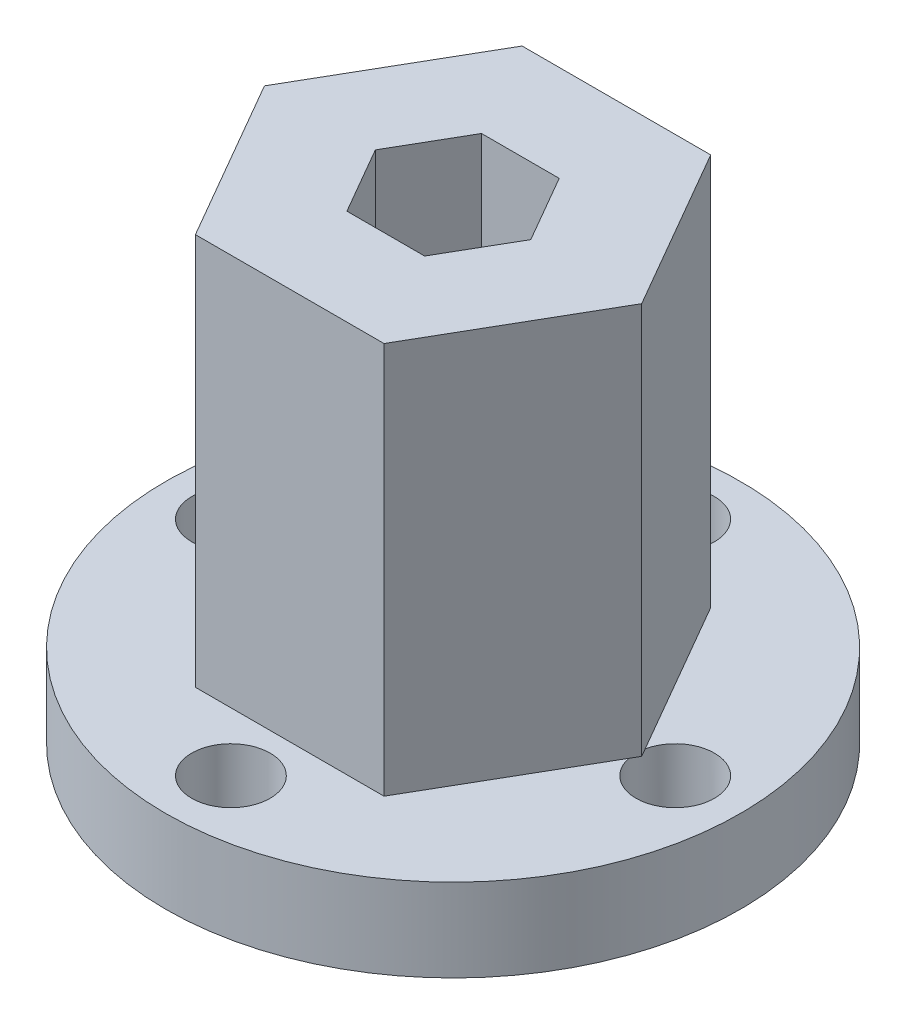
SolidWorks part; units mm, degrees
ref_plane "Front" through (0, 0, 0) normal (0, 0, 1) x (1, 0, 0)
ref_plane "Top" through (0, 0, 0) normal (0, 1, 0) x (1, 0, 0)
ref_plane "Right" through (0, 0, 0) normal (1, 0, 0) x (0, 0, -1)
sketch "Sketch1" plane through (0, 0, 0) normal (0, 1, 0) x (1, 0, 0)
  circle A0 centre (0, 0) radius 11
  dimension "D1" = 22
extrude "Boss-Extrude1" add sketch "Sketch1" along normal blind 3.175
sketch "Sketch2" plane through (0, 3.175, 0) normal (0, 1, 0) x (1, 0, 0)
  line L1 (3.6084, -6.25) -> (7.2169, 0)
  line L2 (7.2169, 0) -> (3.6084, 6.25)
  line L3 (3.6084, 6.25) -> (-3.6084, 6.25)
  line L4 (-3.6084, 6.25) -> (-7.2169, 0)
  line L5 (-7.2169, 0) -> (-3.6084, -6.25)
  line L6 (-3.6084, -6.25) -> (3.6084, -6.25)
  circle A0 centre (0, 0) radius 6.25 construction
  dimension "D1" = 12.5
extrude "Boss-Extrude2" add sketch "Sketch2" along normal blind 15 contours L6 L1 L2 L3 L4 L5
sketch "Sketch3" plane through (0, 18.175, 0) normal (0, 1, 0) x (1, 0, 0)
  line L1 (1.4867, -2.575) -> (2.9734, 0)
  line L2 (2.9734, 0) -> (1.4867, 2.575)
  line L3 (1.4867, 2.575) -> (-1.4867, 2.575)
  line L4 (-1.4867, 2.575) -> (-2.9734, 0)
  line L5 (-2.9734, 0) -> (-1.4867, -2.575)
  line L6 (-1.4867, -2.575) -> (1.4867, -2.575)
  circle A0 centre (0, 0) radius 2.575 construction
  dimension "D1" = 5.15
extrude "Cut-Extrude2" cut sketch "Sketch3" against normal blind 28
sketch "Sketch6" plane through (0, 3.175, 0) normal (0, 1, 0) x (1, 0, 0)
  circle A0 centre (0, 8.5) radius 1.5
  circle A1 centre (0, 0) radius 11 construction
  circle A2 centre (8.5, 0) radius 1.5
  circle A3 centre (0, -8.5) radius 1.5
  circle A4 centre (-8.5, 0) radius 1.5
  point P13 (0, 0)
  dimension "D1" = 8.5
  dimension "D2" = 4
extrude "Cut-Extrude3" cut sketch "Sketch6" against normal blind 8
